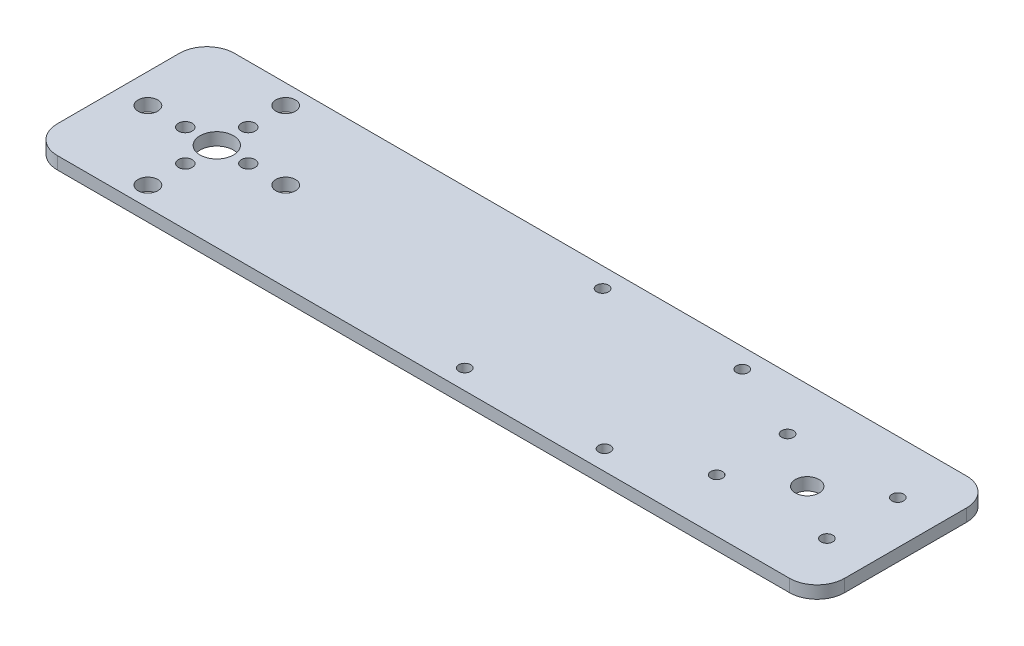
SolidWorks part; units mm, degrees
ref_plane "Front Plane" through (0, 0, 0) normal (0, 0, 1) x (1, 0, 0)
ref_plane "Top Plane" through (0, 0, 0) normal (0, 1, 0) x (1, 0, 0)
ref_plane "Right Plane" through (0, 0, 0) normal (1, 0, 0) x (0, 0, -1)
sketch "Sketch1" plane through (0, 0, 0) normal (0, 1, 0) x (1, 0, 0)
  line L0 (-25, 0) -> (0, 0) construction
  line L1 (-25, 22.5) -> (175, 22.5)
  line L2 (-25, 22.5) -> (-25, -22.5)
  line L3 (-25, -22.5) -> (175, -22.5)
  line L4 (175, 22.5) -> (175, -22.5)
  dimension "D1" = 25
  dimension "D2" = 200
  dimension "D3" = 45
extrude "Boss-Extrude1" add sketch "Sketch1" along normal blind 3.175
sketch "Sketch4" plane through (0, 3.175, 0) normal (0, 1, 0) x (1, 0, 0)
  line L0 (175, 0) -> (-25, 0) construction
  line L1 (175, -22.5) -> (175, 22.5) construction
  line L2 (-25, 22.5) -> (-25, -22.5) construction
  line L3 (150, 22.5) -> (150, -22.5) construction
  line L4 (175, 22.5) -> (-25, 22.5) construction
  line L5 (-25, -22.5) -> (175, -22.5) construction
  circle A0 centre (150, 0) radius 3
  circle A1 centre (136, 9) radius 1.5
  circle A2 centre (164, 9) radius 1.5
  circle A3 centre (164, -9) radius 1.5
  circle A4 centre (136, -9) radius 1.5
  dimension "D1" = 6
  dimension "D5" = 3
  dimension "D2" = 25
  dimension "D3" = 14
  dimension "D4" = 9
extrude "Cut-Extrude1" cut sketch "Sketch4" against normal through all
sketch "Sketch5" plane through (0, 3.175, 0) normal (0, 1, 0) x (1, 0, 0)
  circle A0 centre (0, 0) radius 4.25
  dimension "D1" = 8.5
extrude "Cut-Extrude2" cut sketch "Sketch5" against normal through all
sketch "Sketch10" plane through (0, 3.175, 0) normal (0, 1, 0) x (1, 0, 0)
  line L0 (-25, 0) -> (175, 0) construction
  line L1 (-25, -22.5) -> (175, -22.5) construction
  line L2 (175, -22.5) -> (175, 22.5) construction
  line L3 (-25, 22.5) -> (-25, -22.5) construction
  circle A0 centre (80.5, -17.5) radius 1.5
  circle A1 centre (0, 0) radius 4.25 construction
  circle A2 centre (116, -17.5) radius 1.5
  circle A3 centre (136, -9) radius 1.5 construction
  circle A4 centre (116, 17.5) radius 1.5
  circle A5 centre (80.5, 17.5) radius 1.5
  dimension "D3" = 3
  dimension "D4" = 20
  dimension "D1" = 80.5
  dimension "D2" = 5
extrude "Cut-Extrude4" cut sketch "Sketch10" against normal through all
fillet "Fillet1" radius 7 4 edges at (-25, 1.5875, 22.5) (-25, 1.5875, -22.5) (175, 1.5875, -22.5) (175, 1.5875, 22.5)
sketch "Sketch11" plane through (0, 3.175, 0) normal (0, 1, 0) x (1, 0, 0)
  line L0 (0, 22.5) -> (0, -22.5) construction
  line L1 (168, 22.5) -> (-18, 22.5) construction
  line L2 (-18, -22.5) -> (168, -22.5) construction
  circle A0 centre (0, 17.5) radius 2.5
  circle A2 centre (0, 0) radius 4.25 construction
  circle A3 centre (17.5, 0) radius 2.5
  circle A4 centre (0, -17.5) radius 2.5
  circle A5 centre (-17.5, 0) radius 2.5
  point P3 (0, 0)
  point P12 (0, 0)
  point P13 (0, 0)
  dimension "D1" = 5
  dimension "D2" = 17.5
  dimension "D3" = 4
extrude "Cut-Extrude5" cut sketch "Sketch11" against normal through all
sketch "Sketch12" plane through (0, 3.175, 0) normal (0, 1, 0) x (1, 0, 0)
  circle A0 centre (0, 8) radius 1.75
  circle A1 centre (8, 0) radius 1.75
  circle A2 centre (0, -8) radius 1.75
  circle A3 centre (-8, 0) radius 1.75
  dimension "D1" = 3.5
  dimension "D2" = 8
  dimension "D3" = 4
extrude "Cut-Extrude6" cut sketch "Sketch12" against normal through all
